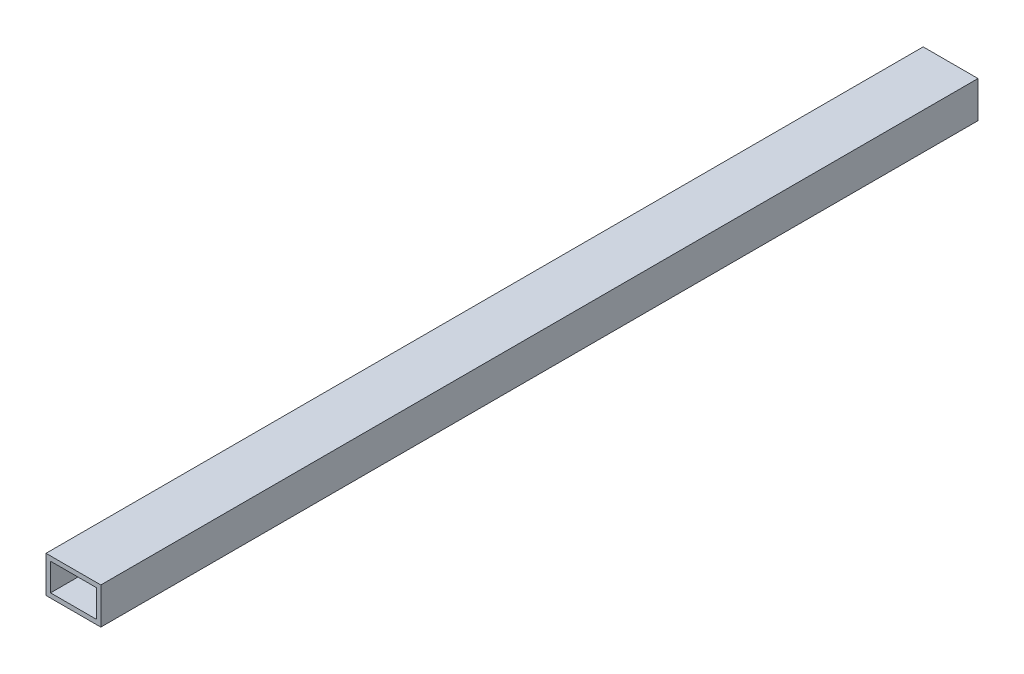
SolidWorks part; units mm, degrees
material "6061 Alloy"
ref_plane "Front Plane" through (0, 0, 0) normal (0, 0, 1) x (1, 0, 0)
ref_plane "Top Plane" through (0, 0, 0) normal (0, 1, 0) x (1, 0, 0)
ref_plane "Right Plane" through (0, 0, 0) normal (1, 0, 0) x (0, 0, -1)
sketch "Sketch1" plane through (0, 0, 0) normal (0, 0, 1) x (1, 0, 0)
  line L0 (19.05, 0) -> (15.875, 0) construction
  line L1 (-19.05, 0) -> (19.05, 0) construction
  line L2 (0, 12.7) -> (0, -12.7)
  point P7 (0, 0)
sketch "Sketch2" plane through (0, 0, 0) normal (1, 0, 0) x (0, 0, -1)
  line L0 (304.8, 0) -> (-304.8, 0)
  point P4 (0, 0)
  dimension "Length" = 609.6
sketch "Sketch3" plane through (0, 0, 0) normal (0, 0, 1) x (1, 0, 0)
  line L0 (-19.05, 0) -> (19.05, 0) construction
  line L5 (19.05, -12.7) -> (-19.05, -12.7)
  line L6 (19.05, -12.7) -> (19.05, 12.7)
  line L11 (19.05, 12.7) -> (-19.05, 12.7)
  line L12 (-19.05, -12.7) -> (-19.05, 12.7)
  line L14 (19.05, -12.7) -> (-19.05, 12.7) construction
  line L15 (19.05, 12.7) -> (-19.05, -12.7) construction
  line L16 (15.875, -9.525) -> (-15.875, -9.525)
  line L17 (15.875, -9.525) -> (15.875, 9.525)
  line L18 (15.875, 9.525) -> (-15.875, 9.525)
  line L19 (-15.875, -9.525) -> (-15.875, 9.525)
  line L20 (15.875, -9.525) -> (-15.875, 9.525) construction
  line L21 (15.875, 9.525) -> (-15.875, -9.525) construction
  point P0 (0, 0)
  point P5 (0, 0)
  point P13 (15.875, -12.7)
  dimension "D1" = 3.175
  dimension "D3" = 38.1
  dimension "D4" = 25.4
  dimension "D2" = 3.175
extrude "Boss-Extrude1" add sketch "Sketch3" along normal up to vertex (304.8 mm away) and the other way up to vertex (304.8 mm away) up to point (0, 0, 304.8) other way up to point (0, 0, -304.8)
sketch "Sketch5" plane through (0, 0, 0) normal (1, 0, 0) x (0, 0, -1)
  line L0 (-304.8, 0) -> (304.8, 0) construction
  line L3 (-304.8, -12.7) -> (-304.8, 12.7) construction
  line L4 (304.8, -12.7) -> (304.8, 12.7) construction
  point P6 (-261.9375, 0)
  point P7 (-247.65, 0)
  point P8 (247.65, 0)
  point P10 (261.9375, 0)
  dimension "D1" = 42.8625
  dimension "D2" = 57.15
  dimension "D3" = 42.8625
  dimension "D4" = 57.15
equation "\"D1@Sketch3\"=\"Wall thickness@Sketch1\""
equation "\"D1@Sketch5\"=\"Width@Sketch1\"*1.125"
equation "\"D2@Sketch5\"=\"Width@Sketch1\"*1.5"
equation "\"D3@Sketch5\"=\"D1@Sketch5\""
equation "\"D4@Sketch5\"=\"D2@Sketch5\""
equation "\"D2@Sketch3\"=\"Wall Thickness@Sketch1\""
